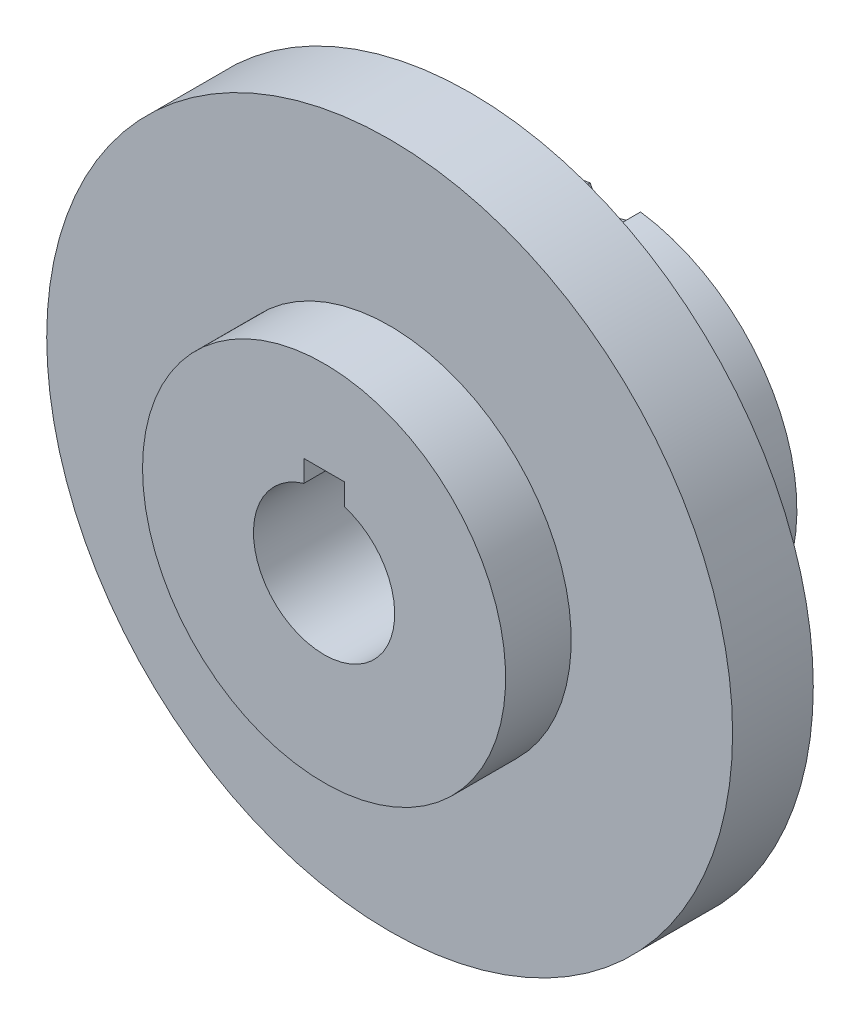
SolidWorks part; units mm, degrees
ref_plane "Спереди" through (0, 0, 0) normal (0, 0, 1) x (1, 0, 0)
ref_plane "Сверху" through (0, 0, 0) normal (0, 1, 0) x (1, 0, 0)
ref_plane "Справа" through (0, 0, 0) normal (1, 0, 0) x (0, 0, -1)
sketch "Эскиз1" plane through (0, 0, 0) normal (0, 0, 1) x (1, 0, 0)
  line L1 (-2, 8.85) -> (2, 8.85)
  line L2 (-2, 8.85) -> (-2, 6.7082)
  line L4 (2, 8.85) -> (2, 6.7082)
  arc A0 (-2, 6.7082) -> (2, 6.7082) centre (0, 0) ccw
  arc A1 (-2.5, 17.8255) -> (-16.6874, -6.7477) centre (0, 0) ccw
  arc A2 (-2.5, 17.8255) -> (2.5, 17.8255) centre (0, 18.9352) ccw
  arc A3 (-16.6874, -6.7477) -> (-14.1874, -11.0778) centre (-16.3984, -9.4676) cw
  arc A4 (14.1874, -11.0778) -> (16.6874, -6.7477) centre (16.3984, -9.4676) cw
  arc A5 (-14.1874, -11.0778) -> (14.1874, -11.0778) centre (0, 0) ccw
  arc A6 (16.6874, -6.7477) -> (2.5, 17.8255) centre (0, 0) ccw
  dimension "D1" = 14
  dimension "D2" = 36
  dimension "D4" = 2.7352
  dimension "D5" = 2.7352
  dimension "D6" = 2.7352
  dimension "D18" = 18
  dimension "D3" = 2
  dimension "D7" = 2
  dimension "D8" = 2.5
  dimension "D9" = 14.1874
  dimension "D10" = 16.3984
  dimension "D11" = 2.5
  dimension "D12" = 14.1874
  dimension "D13" = 16.3984
  dimension "D14" = 8.85
  dimension "D15" = 8.85
  dimension "D16" = 2
  dimension "D17" = 2
extrude "Вытянуть1" add sketch "Эскиз1" along normal up to surface (14.3746 mm away) from offset 6
sketch "Эскиз3" plane through (0, 0, 8.3746) normal (0, 0, 1) x (1, 0, 0)
  line L0 (-2, 8.85) -> (-2, 6.7082)
  line L1 (-2, 8.85) -> (2, 8.85)
  line L2 (2, 8.85) -> (2, 6.7082)
  circle A0 centre (0, 0) radius 34
  arc A1 (-2, 6.7082) -> (2, 6.7082) centre (0, 0) ccw
  dimension "D1" = 68
extrude "Вытянуть2" add sketch "Эскиз3" along normal blind 8
sketch "Эскиз5" plane through (0, 0, 16.3746) normal (0, 0, 1) x (1, 0, 0)
  line L0 (-2, 6.7082) -> (-2, 8.85)
  line L1 (-2, 8.85) -> (2, 8.85)
  line L2 (2, 8.85) -> (2, 6.7082)
  arc A0 (-2, 6.7082) -> (2, 6.7082) centre (0, 0) ccw
  circle A1 centre (0, 0) radius 18
  dimension "D1" = 36
extrude "Вытянуть3" add sketch "Эскиз5" along normal blind 6.5
